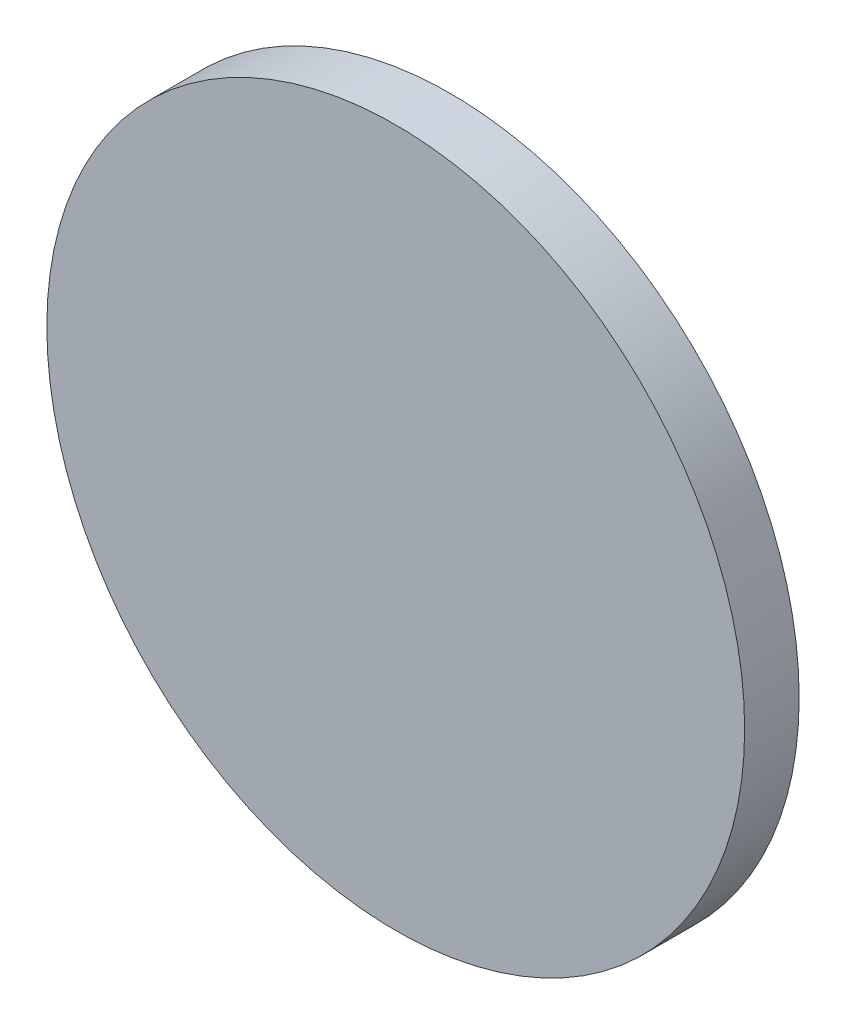
SolidWorks part; units mm, degrees
ref_plane "Front Plane" through (0, 0, 0) normal (0, 0, 1) x (1, 0, 0)
ref_plane "Top Plane" through (0, 0, 0) normal (0, 1, 0) x (1, 0, 0)
ref_plane "Right Plane" through (0, 0, 0) normal (1, 0, 0) x (0, 0, -1)
sketch "Sketch1" plane through (0, 0, 0) normal (0, 0, 1) x (1, 0, 0)
  circle A0 centre (0, 0) radius 64
  dimension "D1" = 128
extrude "Boss-Extrude2" add sketch "Sketch1" along normal blind 10
